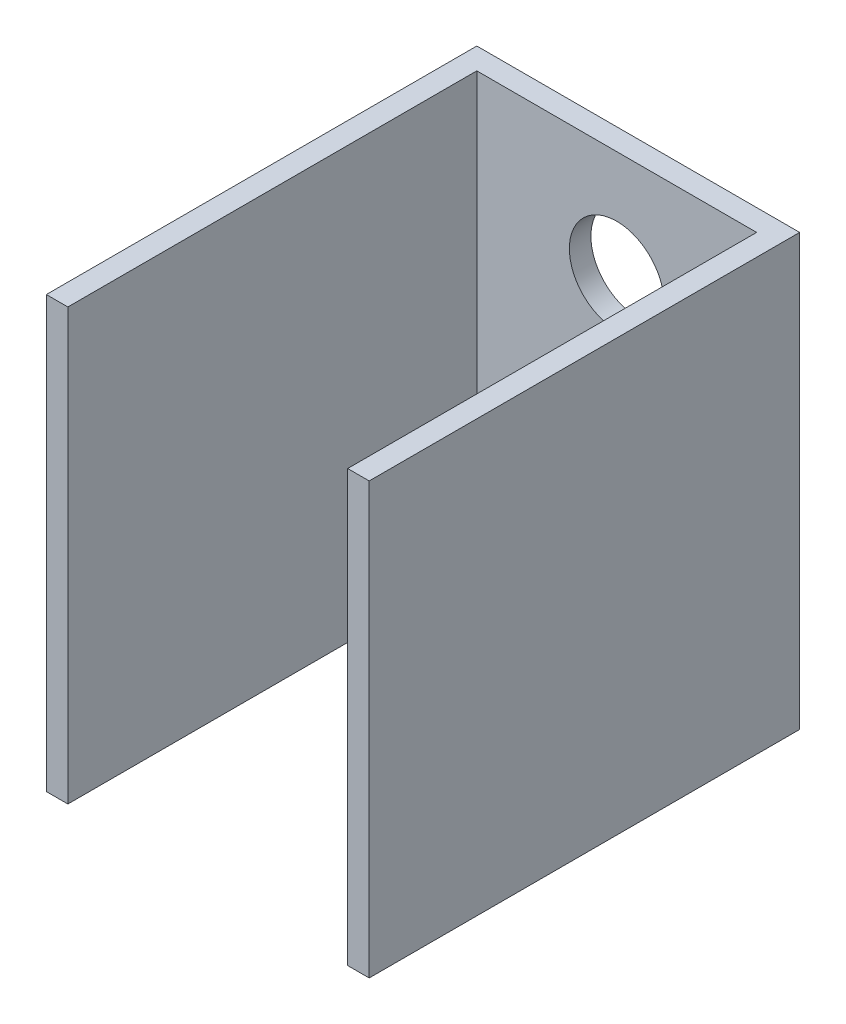
SolidWorks part; units mm, degrees
ref_plane "Front Plane" through (0, 0, 0) normal (0, 0, 1) x (1, 0, 0)
ref_plane "Top Plane" through (0, 0, 0) normal (0, 1, 0) x (1, 0, 0)
ref_plane "Right Plane" through (0, 0, 0) normal (1, 0, 0) x (0, 0, -1)
sketch "Croquis1" plane through (0, 0, 0) normal (0, 1, 0) x (1, 0, 0)
  line L0 (6.5, -10) -> (7.5, -10)
  line L1 (-7.5, -10) -> (-6.5, -10)
  line L2 (-7.5, -10) -> (-7.5, 10)
  line L3 (-7.5, 10) -> (7.5, 10)
  line L4 (7.5, -10) -> (7.5, 10)
  line L12 (-6.5, -10) -> (-6.5, 9)
  line L13 (-6.5, 9) -> (6.5, 9)
  line L14 (6.5, -10) -> (6.5, 9)
  line L15 (0, -0.5) -> (0.1789, -0.2385) construction
  line L20 (0, 0) -> (0.1789, -0.2385) construction
  line L21 (-0.1789, -0.2385) -> (0, -0.5) construction
  line L22 (-0.1789, -0.2385) -> (0, 0) construction
  point P0 (0, 0)
  point P5 (0, 0)
  point P6 (0, -0.5)
  dimension "D1" = 15
  dimension "D2" = 20
  dimension "D3" = 19
  dimension "D4" = 13
extrude "Saliente-Extruir1" add sketch "Croquis1" along normal blind 20
hole_wizard "CBORE for M2 Hex Socket Head Cap Screw1" positions "Croquis2" profile "Croquis3" counterbore size "M2" standard "ISO" end condition up to next
sketch "Croquis2" plane through (0, 0, -9) normal (0, 0, 1) x (1, 0, 0)
  line L4 (0, 0) -> (0, 20) construction
  line L5 (-6.5, 20) -> (6.5, 20) construction
  line L7 (-12.295, 15) -> (11.0044, 15) construction
  point P18 (0, 15)
  dimension "D1" = 5
sketch "Croquis3" plane through (0, 15, -9) normal (1, 0, 0) x (0, -1, 0)
  line L0 (0, 0) -> (0, 1)
  line L1 (0, 1) -> (1.2, 1)
  line L3 (1.2, 1) -> (1.2, 2.4)
  line L4 (1.2, 2.4) -> (2.2, 2.4)
  line L5 (2.2, 2.4) -> (2.2, 0)
  line L7 (2.2, 0) -> (0, 0)
  line L11 (0, -6.35) -> (0, 107.95) construction
  dimension "Thru Hole Dia." = 2.4
  dimension "Thru Hole Depth" = 1
  dimension "C'Bore Dia." = 4.4
  dimension "C'Bore Depth" = 2.4
